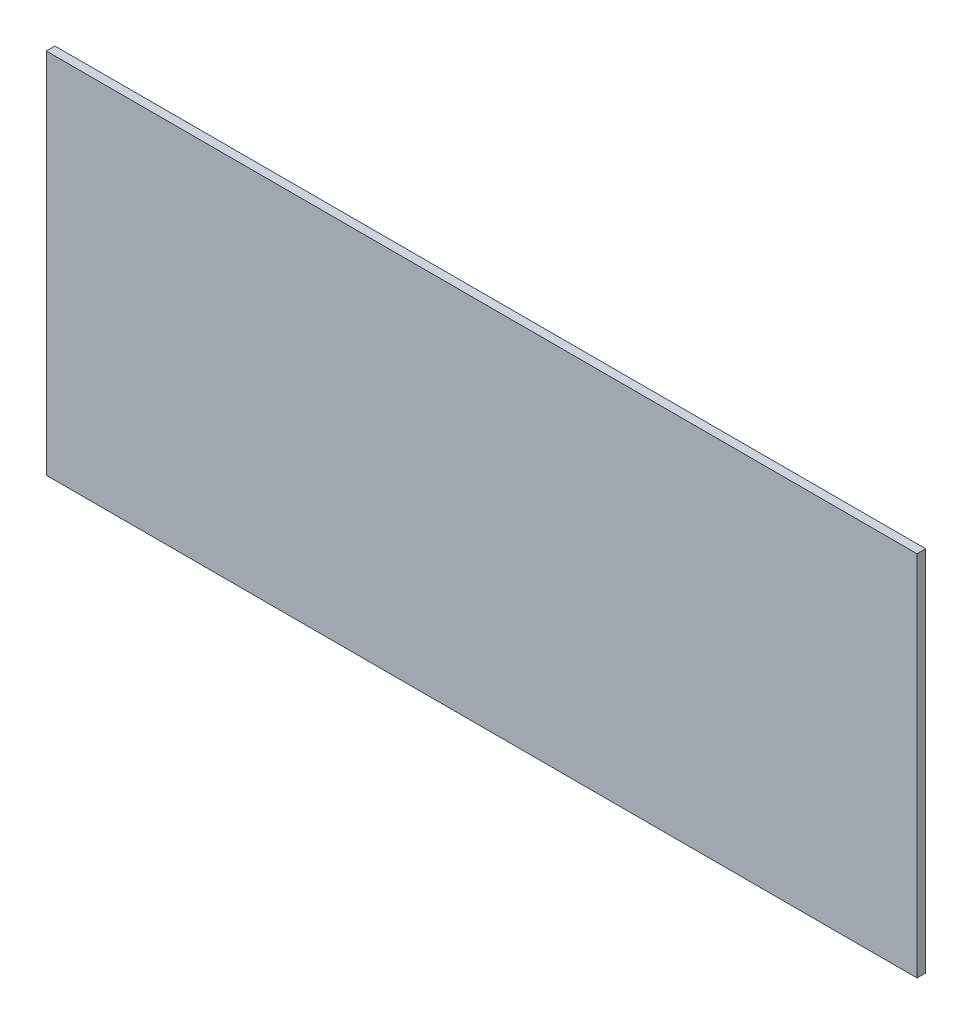
SolidWorks part; units mm, degrees
ref_plane "Plan de face" through (0, 0, 0) normal (0, 0, 1) x (1, 0, 0)
ref_plane "Plan de dessus" through (0, 0, 0) normal (0, 1, 0) x (1, 0, 0)
ref_plane "Plan de droite" through (0, 0, 0) normal (1, 0, 0) x (0, 0, -1)
sketch "Esquisse1" plane through (0, 0, 0) normal (0, 0, 1) x (1, 0, 0)
  line L1 (0, 0) -> (-301, 0)
  line L2 (0, 0) -> (0, 127)
  line L3 (0, 127) -> (-301, 127)
  line L4 (-301, 0) -> (-301, 127)
  dimension "D1" = 127
  dimension "D2" = 301
extrude "Boss.-Extru.1" add sketch "Esquisse1" along normal blind 3
